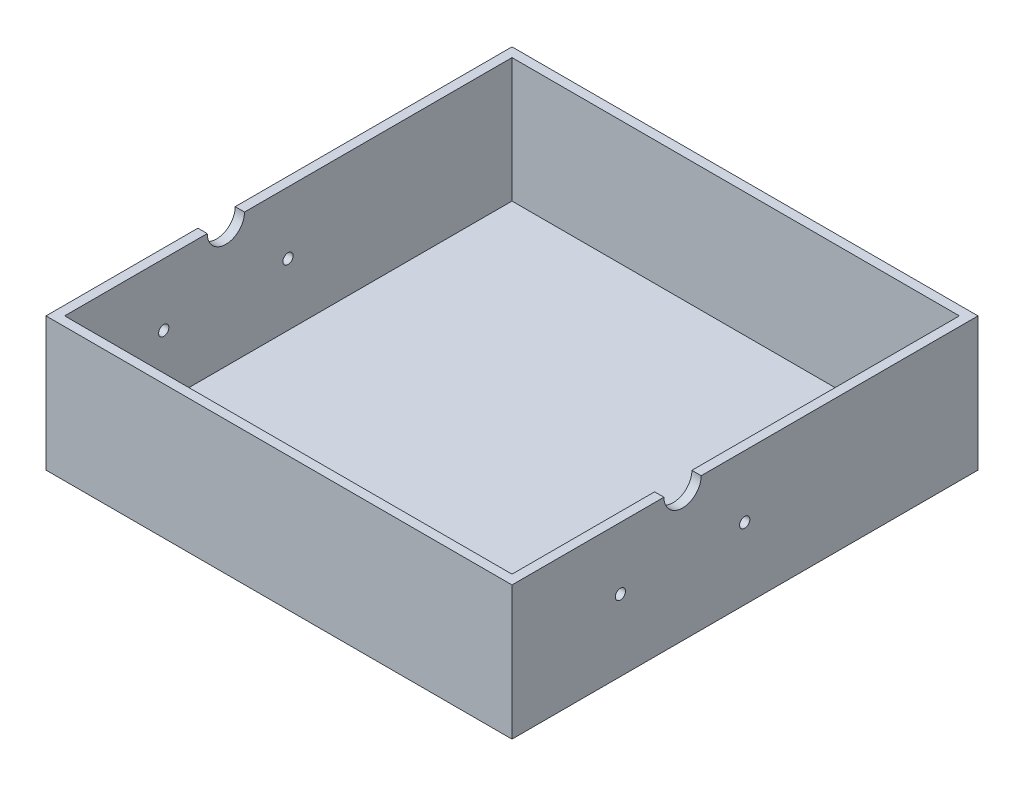
SolidWorks part; units mm, degrees
ref_plane "前视基准面" through (0, 0, 0) normal (0, 0, 1) x (1, 0, 0)
ref_plane "上视基准面" through (0, 0, 0) normal (0, 1, 0) x (1, 0, 0)
ref_plane "右视基准面" through (0, 0, 0) normal (1, 0, 0) x (0, 0, -1)
sketch "草图1" plane through (0, 0, 0) normal (0, 1, 0) x (1, 0, 0)
  line L1 (-75, -75) -> (75, -75)
  line L2 (-75, -75) -> (-75, 75)
  line L3 (-75, 75) -> (75, 75)
  line L4 (75, -75) -> (75, 75)
  line L5 (-75, -75) -> (75, 75) construction
  line L6 (-75, 75) -> (75, -75) construction
  point P0 (0, 0)
  dimension "D1" = 150
  dimension "D2" = 150
extrude "凸台-拉伸1" add sketch "草图1" along normal blind 3
sketch "草图2" plane through (0, 3, 0) normal (0, 1, 0) x (1, 0, 0)
  line L1 (75, -75) -> (-75, -75)
  line L2 (75, -75) -> (75, 75)
  line L3 (75, 75) -> (-75, 75)
  line L4 (-75, -75) -> (-75, 75)
  line L5 (75, -75) -> (-75, 75) construction
  line L6 (75, 75) -> (-75, -75) construction
  line L7 (72, -72) -> (-72, -72)
  line L8 (72, -72) -> (72, 72)
  line L9 (72, 72) -> (-72, 72)
  line L10 (-72, -72) -> (-72, 72)
  line L11 (72, -72) -> (-72, 72) construction
  line L12 (72, 72) -> (-72, -72) construction
  point P1 (0, 0)
  point P7 (0, 0)
  dimension "D1" = 144
extrude "凸台-拉伸2" add sketch "草图2" along normal blind 40
sketch "草图3" plane through (75, 0, 0) normal (1, 0, 0) x (0, 0, -1)
  line L0 (-75, 43) -> (75, 43) construction
  line L1 (-75, 43) -> (-75, 0) construction
  line L2 (-20.1, 37) -> (-20.1, 19.8129) construction
  circle A0 centre (-20.1, 43) radius 6
  circle A1 centre (-0.1, 23) radius 1.65
  circle A2 centre (-40.1, 23) radius 1.65
  dimension "D2" = 12
  dimension "D3" = 3.3
  dimension "D4" = 3.3
  dimension "D1" = 54.9
  dimension "D5" = 40
  dimension "D6" = 20
extrude "切除-拉伸1" cut sketch "草图3" against normal through all
